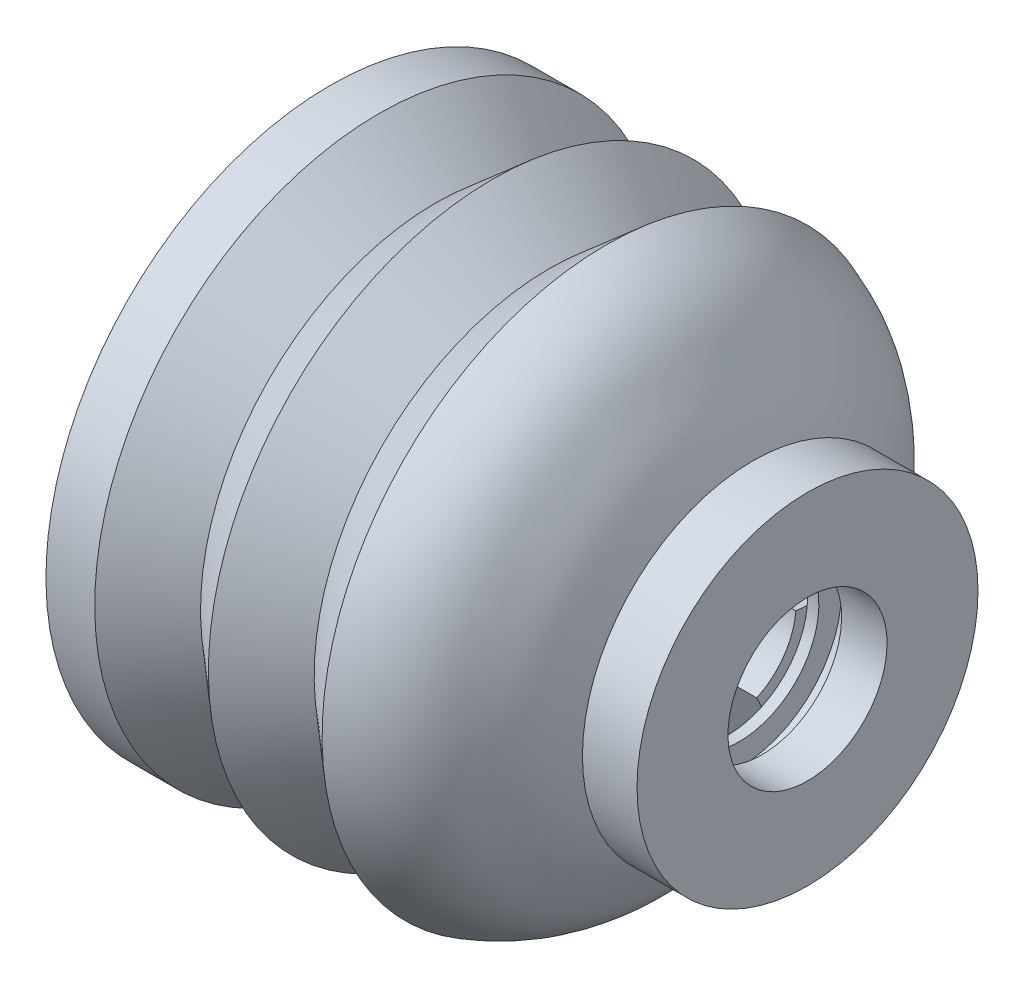
SolidWorks part; units mm, degrees
ref_plane "前视基准面" through (0, 0, 0) normal (0, 0, 1) x (1, 0, 0)
ref_plane "上视基准面" through (0, 0, 0) normal (0, 1, 0) x (1, 0, 0)
ref_plane "右视基准面" through (0, 0, 0) normal (1, 0, 0) x (0, 0, -1)
sketch "草图1" plane through (0, 0, 0) normal (0, 0, 1) x (1, 0, 0)
  line L0 (7.7591, -12.7364) -> (-74.4223, -12.7364) construction
  line L1 (-4.9811, -19.7364) -> (-8.9811, -19.7364)
  line L2 (-8.9811, -19.7364) -> (-8.9811, -21.7364)
  line L3 (-8.9811, -21.7364) -> (-10.9811, -21.7364)
  line L4 (-10.9811, -21.7364) -> (-10.9811, -19.7364)
  line L5 (-10.9811, -19.7364) -> (-11.9811, -19.7364)
  line L6 (-4.9811, -19.7364) -> (-4.9811, -27.7364)
  line L7 (-4.9811, -27.7364) -> (-9.7811, -27.7364)
  line L8 (-9.7811, -27.7364) -> (-11.9811, -23.5364)
  line L9 (-22.6898, -37.7364) -> (-27.6898, -33.4313)
  line L10 (-27.6898, -33.4313) -> (-32.6898, -37.7364)
  line L11 (-32.6898, -37.7364) -> (-37.6898, -33.4313)
  line L12 (-37.6898, -33.4313) -> (-42.6898, -37.7364)
  line L13 (-42.6898, -37.7364) -> (-46.9811, -37.7364)
  line L14 (-25.2292, -33.4313) -> (-43.9892, -33.4313) construction
  line L16 (-22.6898, -37.7364) -> (-41.8627, -37.7364) construction
  line L17 (-22.6898, -34.0415) -> (-26.1677, -31.0469)
  line L18 (-29.2119, -31.0469) -> (-32.6898, -34.0415)
  line L19 (-32.6898, -34.0415) -> (-36.1677, -31.0469)
  line L20 (-39.2119, -31.0469) -> (-46.9811, -37.7364)
  line L21 (-37.6898, -29.7364) -> (-44.5167, -35.6145) construction
  line L22 (-27.6898, -29.7364) -> (-32.6898, -34.0415) construction
  line L23 (-20.8628, -35.6145) -> (-27.6898, -29.7364) construction
  line L24 (-32.6898, -34.0415) -> (-37.6898, -29.7364) construction
  arc A0 (-29.2119, -31.0469) -> (-26.1677, -31.0469) centre (-27.6898, -32.8147) cw
  arc A1 (-39.2119, -31.0469) -> (-36.1677, -31.0469) centre (-37.6898, -32.8147) cw
  spline S0 degree 3 poles (-11.9811, -23.5364) (-13.2181, -28.1935) (-13.9498, -29.2428) (-17.4436, -35.1732) (-19.9348, -36.8156) (-22.6898, -37.7364) knots 0 0 0 0 0.485974 0.585974 1 1 1 1
  spline S1 degree 2 poles (-11.9811, -19.7364) (-14.1051, -29.8368) (-22.6898, -34.0415) knots 0 0 0 1 1 1
  point P3 (-33.3316, -12.7364)
  point P22 (-23.8278, -33.8297)
  point P23 (-28.9664, -21.9551)
  point P27 (-38.9396, -16.5728)
  point P28 (-44.1295, -33.0239)
  dimension "D12" = 2.3327
  dimension "D3" = 2.8
  dimension "D2" = 4
  dimension "D4" = 10
  dimension "D5" = 25
  dimension "D6" = 42
  dimension "D7" = 2
  dimension "D8" = 2
  dimension "D9" = 7
  dimension "D10" = 7
  dimension "D11" = 8
  dimension "D13" = 4.8
  dimension "D14" = 3.8
revolve "旋转2" add sketch "草图1" angle 360 about L0
ref_axis "基准轴1" through (-56.1219, -12.7364, 0) along (1, 0, 0)
ref_plane "基准面1" through (0, -12.6396, 1.1058) normal (0, -0.9962, 0.0872) x (1, 0, 0)
sketch "草图3" plane through (0, -12.6396, 1.1058) normal (0, -0.9962, 0.0872) x (1, 0, 0)
  line L0 (-4.9811, -16.11) -> (-4.9811, 13.89) construction
  line L1 (-4.9811, -16.11) -> (-4.9811, 13.89) construction
  line L2 (-4.9811, -1.11) -> (-73.5144, -1.11) construction
  line L3 (-11.9811, 5.89) -> (-11.9811, -8.11) construction
  line L4 (-11.9811, 5.89) -> (-11.9811, -8.7684) construction
  line L7 (-11.9811, -8.7684) -> (-11.9811, -7.11)
  line L8 (-11.9811, -7.11) -> (-18.9811, -7.11)
  line L9 (-18.9811, -7.11) -> (-18.9811, -21.2912)
  spline S0 degree 3 poles (-11.9811, -8.7684) (-12.6268, -12.1936) (-14.6903, -16.7998) (-17.609, -20.331) (-18.9811, -21.2912) knots 0 0 0 0 0.528345 0.796807 0.796807 0.796807 0.796807
  dimension "D1" = 6
  dimension "D2" = 7
revolve "旋转4" add sketch "草图3" angle 60 about L2
pattern_circular "阵列(圆周)1" count 4 over 360 about axis through (-56.1219, -12.7364, 0) along (1, 0, 0) of bodies 109
combine bodies "组合1" bodies to combine 107 110 109 111 112
sketch "草图5" plane through (0, -12.6396, 1.1058) normal (0, -0.9962, 0.0872) x (1, 0, 0)
  line L0 (-11.9811, 4.89) -> (-14.9811, 4.89) construction
  line L1 (-11.9811, 4.89) -> (-18.9811, 4.89) construction
  line L2 (-14.9811, 4.89) -> (-17.4811, 4.89)
  line L3 (-16.2311, 4.89) -> (-16.2311, -2.4137) construction
  line L4 (-11.9811, -1.11) -> (-11.9811, 4.9521) construction
  spline S0 degree 2 poles (-14.9811, 4.89) (-16.2311, 4.09) (-17.4811, 4.89) knots 0 0 0 1 1 1
  dimension "D1" = 0.4
  dimension "D2" = 4.25
  dimension "D3" = 2.5
revolve "旋转5" add sketch "草图5" angle 360 about axis through (-56.1219, -12.7364, 0) along (1, 0, 0)
